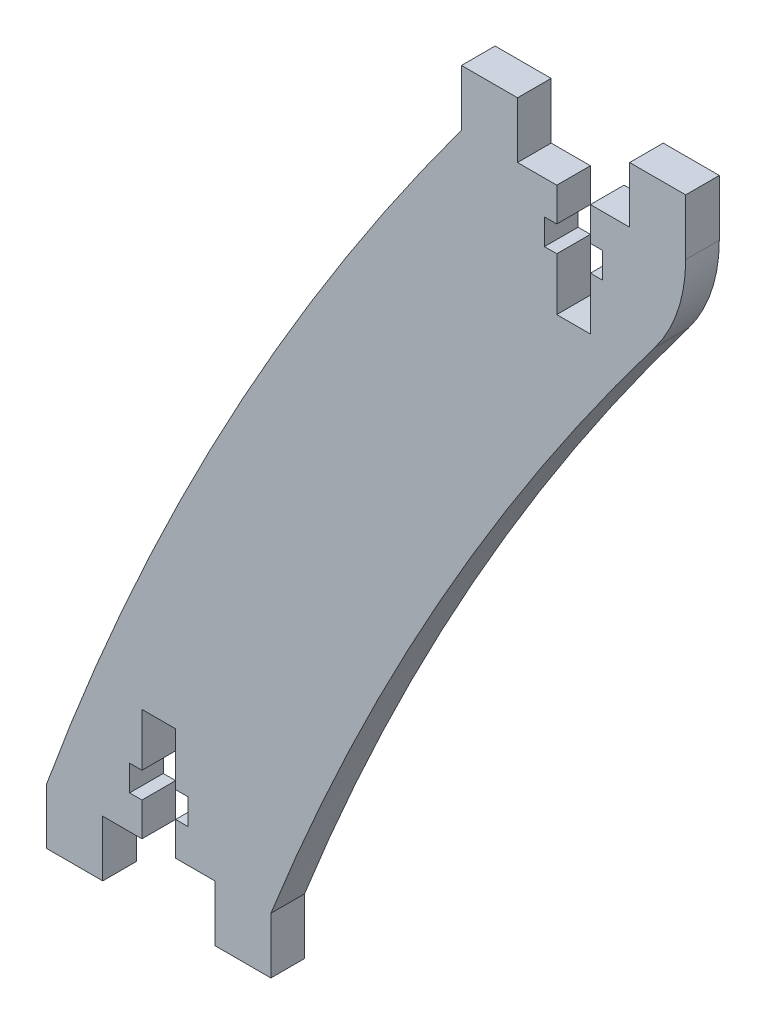
SolidWorks part; units mm, degrees
ref_plane "Front Plane" through (0, 0, 0) normal (0, 0, 1) x (1, 0, 0)
ref_plane "Top Plane" through (0, 0, 0) normal (0, 1, 0) x (1, 0, 0)
ref_plane "Right Plane" through (0, 0, 0) normal (1, 0, 0) x (0, 0, -1)
sketch "Sketch1" plane through (0, 0, 0) normal (0, 0, 1) x (1, 0, 0)
  line L0 (13, 0) -> (13, 69) construction
  line L1 (23, 0) -> (23, 65.2704) construction
  line L2 (13, 69) -> (70, 69) construction
  line L3 (13, 0) -> (21.9506, 24.5916) construction
  line L4 (0, 0) -> (61.5031, 0) construction
  line L5 (70, 69) -> (70, 49.2739) construction
  line L6 (60, 69) -> (60, 55.7792) construction
  line L7 (61.5, 69) -> (65, 69)
  line L8 (65, 74) -> (70, 74)
  line L9 (70, 74) -> (70, 69)
  line L10 (65, 74) -> (65, 69)
  line L11 (58.5, 69) -> (55, 69)
  line L12 (55, 69) -> (55, 74)
  line L13 (55, 74) -> (50, 74)
  line L14 (50, 74) -> (50, 69)
  line L15 (61.5, 69) -> (58.5, 69) construction
  line L16 (58.5, 69) -> (58.5, 66)
  line L17 (58.5, 63.7) -> (57.4, 63.7)
  line L18 (62.6, 66) -> (62.6, 63.7)
  line L19 (57.4, 66) -> (58.5, 66)
  line L20 (58.5, 63.7) -> (58.5, 59)
  line L21 (58.5, 59) -> (61.5, 59)
  line L22 (61.5, 59) -> (61.5, 63.7)
  line L23 (61.5, 66) -> (62.6, 66)
  line L24 (57.4, 63.7) -> (57.4, 66)
  line L25 (62.6, 63.7) -> (61.5, 63.7)
  line L26 (61.5, 66) -> (61.5, 69)
  line L27 (60, 59) -> (60, 69) construction
  line L28 (23, 0) -> (23, 11.2208) construction
  line L29 (21.5, 0) -> (18, 0)
  line L30 (18, -5) -> (13, -5)
  line L31 (13, -5) -> (13, 0)
  line L32 (18, -5) -> (18, 0)
  line L33 (24.5, 0) -> (28, 0)
  line L34 (28, 0) -> (28, -5)
  line L35 (28, -5) -> (33, -5)
  line L36 (33, -5) -> (33, 0)
  line L37 (21.5, 0) -> (24.5, 0) construction
  line L38 (24.5, 0) -> (24.5, 3)
  line L39 (24.5, 5.3) -> (25.6, 5.3)
  line L40 (20.4, 3) -> (20.4, 5.3)
  line L41 (25.6, 3) -> (24.5, 3)
  line L42 (24.5, 5.3) -> (24.5, 10)
  line L43 (24.5, 10) -> (21.5, 10)
  line L44 (21.5, 10) -> (21.5, 5.3)
  line L45 (21.5, 3) -> (20.4, 3)
  line L46 (25.6, 5.3) -> (25.6, 3)
  line L47 (20.4, 5.3) -> (21.5, 5.3)
  line L48 (21.5, 3) -> (21.5, 0)
  line L49 (23, 10) -> (23, 0) construction
  arc A0 (13, 0) -> (50, 69) centre (270.8652, -93.8553) cw
  arc A1 (70, 69) -> (67.2512, 60.8379) centre (56.5079, 69) cw
  arc A2 (67.2512, 60.8379) -> (33, 0) centre (270.8652, -93.8553) ccw
  dimension "D1" = 69
  dimension "D2" = 23
  dimension "D3" = 5.2
  dimension "D4" = 20
  dimension "D5" = 10
  dimension "D6" = 5
  dimension "D7" = 5
  dimension "D8" = 3
  dimension "D9" = 2.3
  dimension "D10" = 3
  dimension "D11" = 10
  dimension "D12" = 10
  dimension "D13" = 5
  dimension "D14" = 5
  dimension "D15" = 5.2
  dimension "D16" = 3
  dimension "D17" = 2.3
  dimension "D18" = 3
  dimension "D19" = 10
  dimension "D20" = 60
extrude "Boss-Extrude1" add sketch "Sketch1" along normal blind 3
